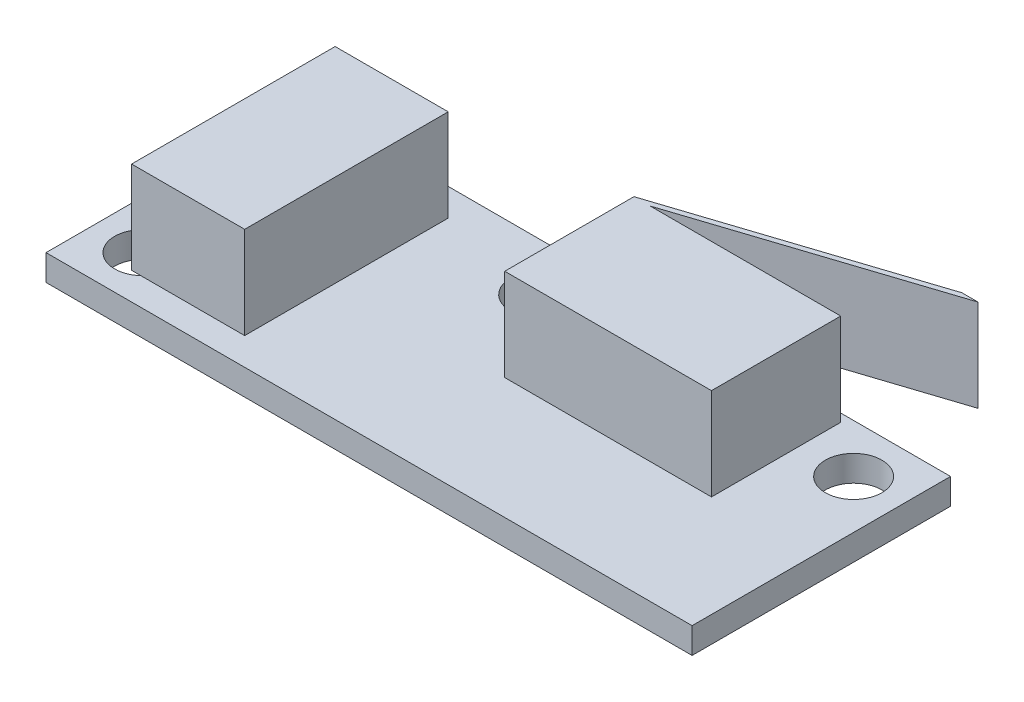
SolidWorks part; units mm, degrees
ref_plane "Front Plane" through (0, 0, 0) normal (0, 0, 1) x (1, 0, 0)
ref_plane "Top Plane" through (0, 0, 0) normal (0, 1, 0) x (1, 0, 0)
ref_plane "Right Plane" through (0, 0, 0) normal (1, 0, 0) x (0, 0, -1)
sketch "Sketch1" plane through (0, 0, 0) normal (0, 1, 0) x (1, 0, 0)
  line L1 (-20, 8) -> (20, 8)
  line L2 (-20, 8) -> (-20, -8)
  line L3 (-20, -8) -> (20, -8)
  line L4 (20, 8) -> (20, -8)
  line L5 (-20, 8) -> (20, -8) construction
  line L6 (-20, -8) -> (20, 8) construction
  point P0 (0, 0)
  dimension "D1" = 40
  dimension "D2" = 16
extrude "Boss-Extrude1" add sketch "Sketch1" along normal blind 1.6
sketch "Sketch2" plane through (0, 0, 0) normal (0, 1, 0) x (1, 0, 0)
  line L0 (20, 8) -> (-20, 8) construction
  line L1 (-20, 8) -> (-20, -8) construction
  line L2 (-20, -8) -> (20, -8) construction
  line L3 (20, -8) -> (20, 8) construction
  circle A0 centre (-17, 5) radius 1.75
  circle A1 centre (-17, -5) radius 1.75
  circle A2 centre (-2.5, 5) radius 1.75
  circle A3 centre (17, 5) radius 1.75
  dimension "D1" = 3.5
  dimension "D2" = 3.5
  dimension "D3" = 3.5
  dimension "D4" = 3.5
  dimension "D5" = 3
  dimension "D6" = 3
  dimension "D7" = 3
  dimension "D8" = 3
  dimension "D9" = 3
  dimension "D10" = 3
  dimension "D11" = 3
  dimension "D12" = 17.5
extrude "Cut-Extrude1" cut sketch "Sketch2" along normal blind 1.6
sketch "Sketch3" plane through (0, 1.6, 0) normal (0, 1, 0) x (1, 0, 0)
  line L0 (0.9, 7.5) -> (16.2, 12.5)
  line L1 (1.9, 7.5) -> (13.7, 7.5)
  line L2 (0.9, 7.5) -> (0.9, -0.5)
  line L3 (0.9, -0.5) -> (13.7, -0.5)
  line L4 (13.7, 7.5) -> (13.7, -0.5)
  line L5 (16.2, 12.5) -> (17.2, 12.5)
  line L6 (17.2, 12.5) -> (1.9, 7.5)
  line L7 (20, 8) -> (-20, 8) construction
  line L8 (20, -8) -> (20, 8) construction
  dimension "D1" = 0.5
  dimension "D2" = 8
  dimension "D3" = 12.8
  dimension "D4" = 6.3
  dimension "D5" = 5
  dimension "D6" = 1
  dimension "D7" = 1
  dimension "D8" = 3.5
  dimension "D9" = 8
extrude "Boss-Extrude2" add sketch "Sketch3" along normal blind 5.7
sketch "Sketch4" plane through (0, 1.6, 0) normal (0, 1, 0) x (1, 0, 0)
  line L0 (-4.015, 0) -> (4.015, 0) construction
  line L1 (-16.4, 6.3) -> (-9.4, 6.3)
  line L2 (-16.4, 6.3) -> (-16.4, -6.3)
  line L3 (-16.4, -6.3) -> (-9.4, -6.3)
  line L4 (-9.4, 6.3) -> (-9.4, -6.3)
  line L5 (-20, 8) -> (-20, -8) construction
  dimension "D1" = 7
  dimension "D2" = 12.6
  dimension "D3" = 6.3
  dimension "D4" = 3.6
extrude "Boss-Extrude3" add sketch "Sketch4" along normal blind 5.7
